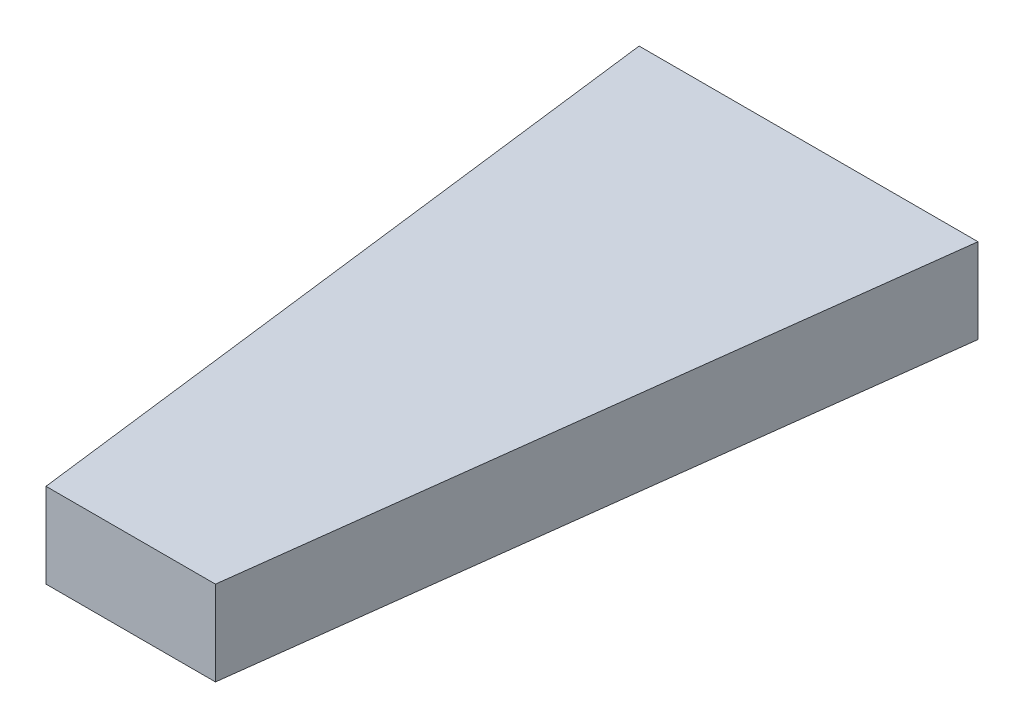
SolidWorks part; units mm, degrees
ref_plane "Front Plane" through (0, 0, 0) normal (0, 0, 1) x (1, 0, 0)
ref_plane "Top Plane" through (0, 0, 0) normal (0, 1, 0) x (1, 0, 0)
ref_plane "Right Plane" through (0, 0, 0) normal (1, 0, 0) x (0, 0, -1)
sketch "Sketch1" plane through (0, 0, 0) normal (0, 1, 0) x (1, 0, 0)
  line L0 (-25.4, 0) -> (25.4, 0)
  line L1 (25.4, 0) -> (12.7, -101.6)
  line L2 (12.7, -101.6) -> (-12.7, -101.6)
  line L3 (-12.7, -101.6) -> (-25.4, 0)
  line L4 (0, 0) -> (0, -101.6) construction
  dimension "D1" = 50.8
  dimension "D2" = 25.4
  dimension "D3" = 101.6
extrude "Boss-Extrude1" add sketch "Sketch1" along normal blind 12.7
